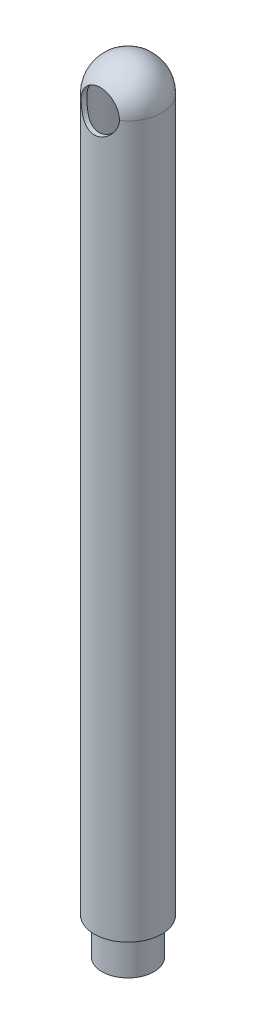
SolidWorks part; units mm, degrees
material "Chrome Stainless Steel"
ref_plane "Plano frontal" through (0, 0, 0) normal (0, 0, 1) x (1, 0, 0)
ref_plane "Plano superior" through (0, 0, 0) normal (0, 1, 0) x (1, 0, 0)
ref_plane "Plano direito" through (0, 0, 0) normal (1, 0, 0) x (0, 0, -1)
sketch "Sketch1" plane through (0, 0, 0) normal (0, 0, 1) x (1, 0, 0)
  line L0 (0, 0) -> (0, 893.401) construction
  line L1 (28.5, 0) -> (28.5, 40)
  line L2 (28.5, 40) -> (37, 40)
  line L3 (37, 40) -> (37, 821)
  line L4 (23.5, 0) -> (23.5, 45)
  line L5 (23.5, 45) -> (32, 45)
  line L6 (32, 45) -> (32, 821)
  line L7 (28.5, 0) -> (23.5, 0)
  line L8 (32, 45) -> (32, 821) construction
  line L9 (0, 858) -> (0, 853)
  arc A0 (37, 821) -> (0, 858) centre (0, 821) ccw
  arc A1 (32, 821) -> (0, 853) centre (0, 821) ccw
  dimension "D6" = 37
  dimension "D1" = 57
  dimension "D2" = 40
  dimension "D3" = 74
  dimension "D5" = 781
  dimension "D4" = 5
  dimension "D7" = 5
revolve "Revolve1" add sketch "Sketch1" angle 360 about L0
sketch "Sketch2" plane through (0, 0, 0) normal (0, 0, 1) x (1, 0, 0)
  line L0 (37, 821) -> (-37, 821) construction
  circle A0 centre (0, 821) radius 21
  dimension "D1" = 42
extrude "Cut-Extrude1" cut sketch "Sketch2" against normal through all both and the other way through all
